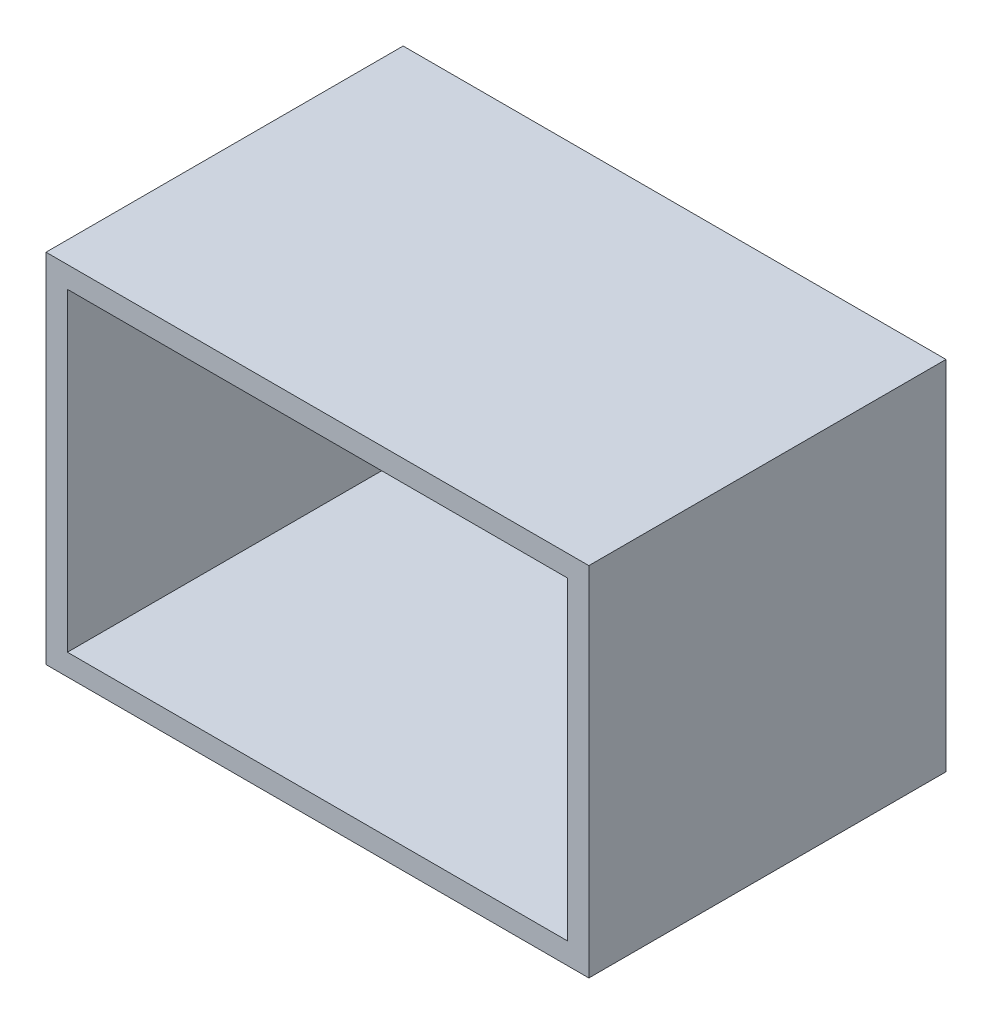
SolidWorks part; units mm, degrees
ref_plane "前视基准面" through (0, 0, 0) normal (0, 0, 1) x (1, 0, 0)
ref_plane "上视基准面" through (0, 0, 0) normal (0, 1, 0) x (1, 0, 0)
ref_plane "右视基准面" through (0, 0, 0) normal (1, 0, 0) x (0, 0, -1)
other "Configuration Table"
sketch "草图1" plane through (0, 0, 0) normal (0, 0, 1) x (1, 0, 0)
  line L1 (-35, -22) -> (35, -22)
  line L2 (-35, -22) -> (-35, 22)
  line L3 (-35, 22) -> (35, 22)
  line L4 (35, -22) -> (35, 22)
  line L5 (-35, -22) -> (35, 22) construction
  line L6 (-35, 22) -> (35, -22) construction
  line L7 (-38, -25) -> (38, -25)
  line L8 (-38, -25) -> (-38, 25)
  line L9 (-38, 25) -> (38, 25)
  line L10 (38, -25) -> (38, 25)
  line L11 (-38, -25) -> (38, 25) construction
  line L12 (-38, 25) -> (38, -25) construction
  point P0 (0, 0)
  point P6 (0, 0)
  dimension "D1" = 70
  dimension "D2" = 44
  dimension "D3" = 3
  dimension "D4" = 3
extrude "凸台-拉伸1" add sketch "草图1" along normal blind 50
